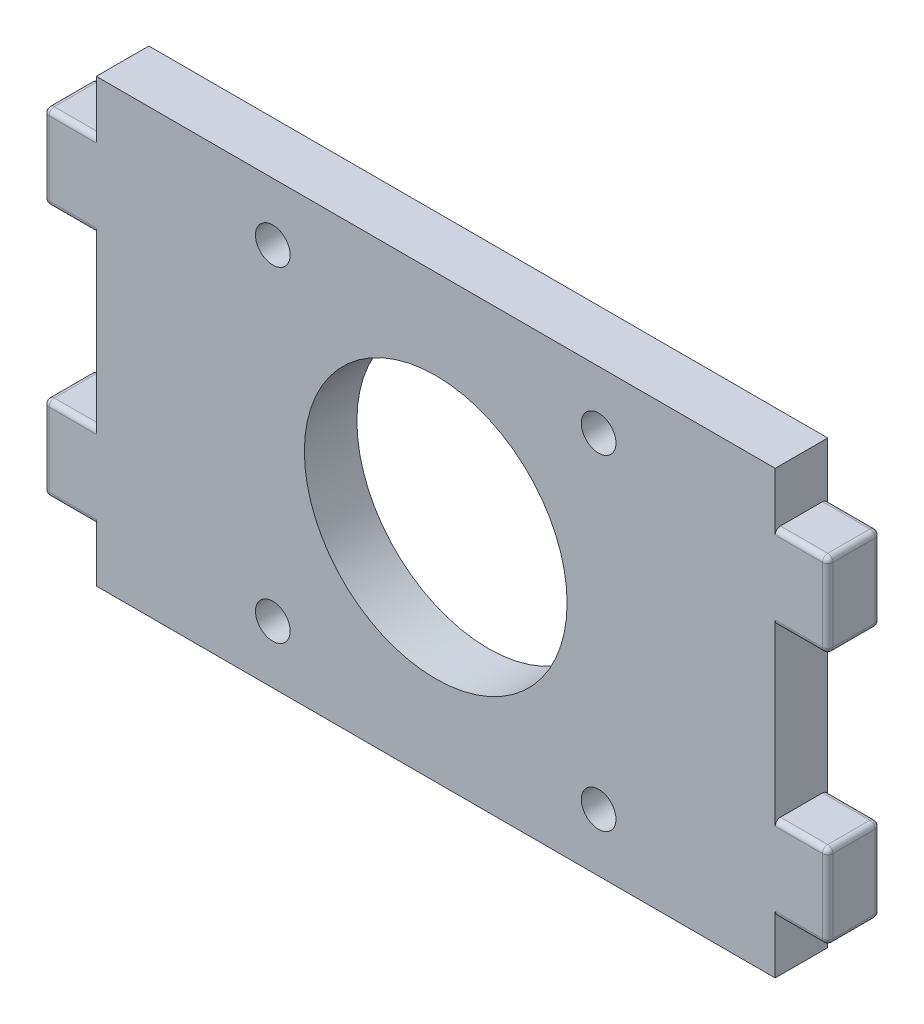
SolidWorks part; units mm, degrees
ref_plane "Alzado" through (0, 0, 0) normal (0, 0, 1) x (1, 0, 0)
ref_plane "Planta" through (0, 0, 0) normal (0, 1, 0) x (1, 0, 0)
ref_plane "Vista lateral" through (0, 0, 0) normal (1, 0, 0) x (0, 0, -1)
sketch "Croquis1" plane through (0, 0, 0) normal (0, 0, 1) x (1, 0, 0)
  line L1 (32.3, -21) -> (-32.3, -21)
  line L2 (32.3, -21) -> (32.3, 21)
  line L3 (32.3, 21) -> (-32.3, 21)
  line L4 (-32.3, -21) -> (-32.3, 21)
  line L5 (32.3, -21) -> (-32.3, 21) construction
  line L6 (32.3, 21) -> (-32.3, -21) construction
  circle A0 centre (-15.5, 15.5) radius 1.65
  circle A1 centre (15.5, 15.5) radius 1.65
  circle A2 centre (0, 0) radius 12.5
  circle A3 centre (-15.5, -15.5) radius 1.65
  circle A4 centre (15.5, -15.5) radius 1.65
  point P0 (0, 0)
  dimension "D5" = 3.3
  dimension "D8" = 25
  dimension "D1" = 64.6
  dimension "D2" = 42
  dimension "D3" = 31
  dimension "D4" = 31
  dimension "D6" = 15.5
  dimension "D7" = 15.5
  dimension "D9" = 0
extrude "Saliente-Extruir1" add sketch "Croquis1" along normal blind 5
sketch "Croquis2" plane through (-32.3, 0, 0) normal (-1, 0, 0) x (0, 0, 1)
  line L0 (0, 21) -> (0, -21) construction
  line L1 (0, 16) -> (5, 16)
  line L2 (0, 16) -> (0, 8)
  line L3 (0, 8) -> (5, 8)
  line L4 (5, 16) -> (5, 8)
  line L5 (5, 21) -> (5, -21) construction
  line L8 (0, -8) -> (5, -8)
  line L9 (0, -8) -> (0, -16)
  line L10 (0, -16) -> (5, -16)
  line L11 (5, -8) -> (5, -16)
  point P14 (5, 12)
  point P15 (5, -12)
  dimension "D1" = 8
  dimension "D3" = 8
  dimension "D4" = 24
  dimension "D2" = 12
extrude "Saliente-Extruir2" add sketch "Croquis2" along normal blind 5
fillet "Redondeo1" radius 0.5 16 edges at (-37.3, -8, 2.5) (-37.3, -12, 5) (-37.3, -16, 2.5) (-37.3, -12, 0) (-37.3, 16, 2.5) (-37.3, 12, 5) (-37.3, 8, 2.5) (-37.3, 12, 0) (-34.8, -16, 0) (-34.8, -16, 5) (-34.8, -8, 0) (-34.8, -8, 5) (-34.8, 8, 0) (-34.8, 8, 5) (-34.8, 16, 0) (-34.8, 16, 5)
mirror "Simetría1" about plane through (0, 0, 0) normal (1, 0, 0) of "Redondeo1", "Saliente-Extruir2"
equation "\"D4@Croquis2\"=\"D2@Croquis2\"*2"
